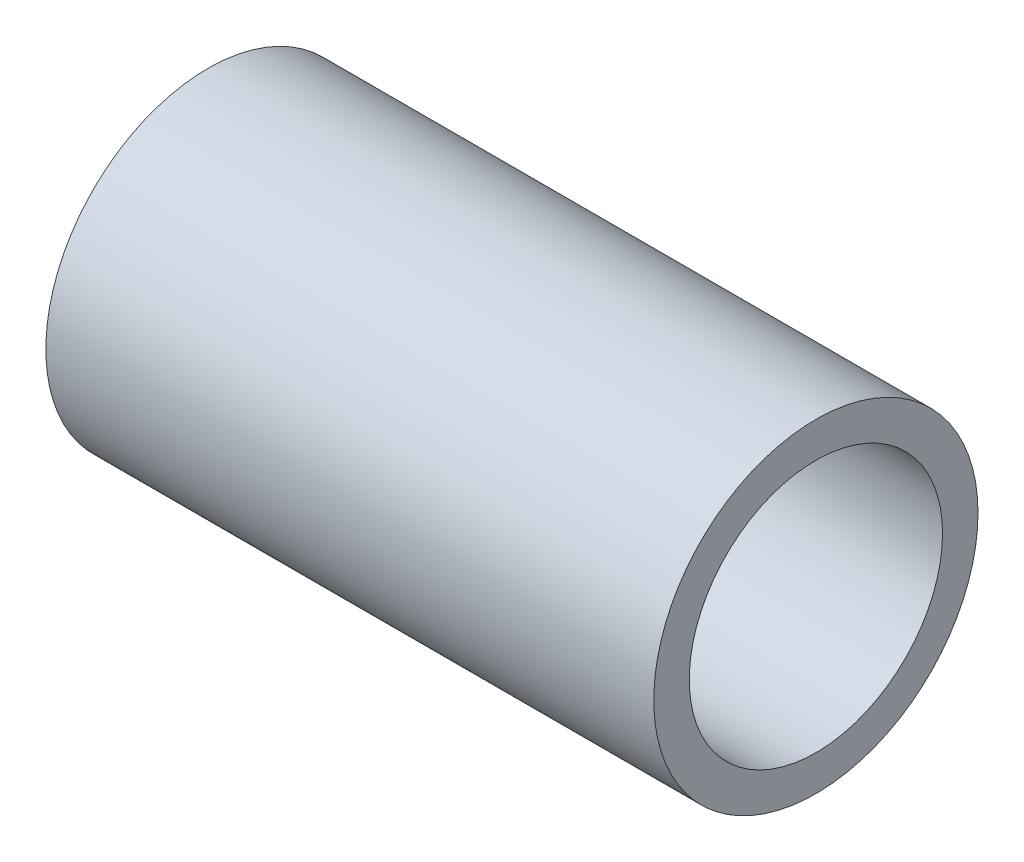
SolidWorks part; units mm, degrees
ref_plane "正面" through (0, 0, 0) normal (0, 0, 1) x (1, 0, 0)
ref_plane "平面" through (0, 0, 0) normal (0, 1, 0) x (1, 0, 0)
ref_plane "右側面" through (0, 0, 0) normal (1, 0, 0) x (0, 0, -1)
sketch "ｽｹｯﾁ1" plane through (0, 0, 0) normal (1, 0, 0) x (0, 0, -1)
  circle A0 centre (0, 0) radius 6.25
  circle A1 centre (0, 0) radius 8
  dimension "D1" = 12.5
  dimension "D2" = 16
extrude "ﾎﾞｽ - 押し出し1" add sketch "ｽｹｯﾁ1" along normal blind 30
equation "\"長さ\"= 30"
equation "\"D1@ﾎﾞｽ - 押し出し1\"=\"長さ\""
